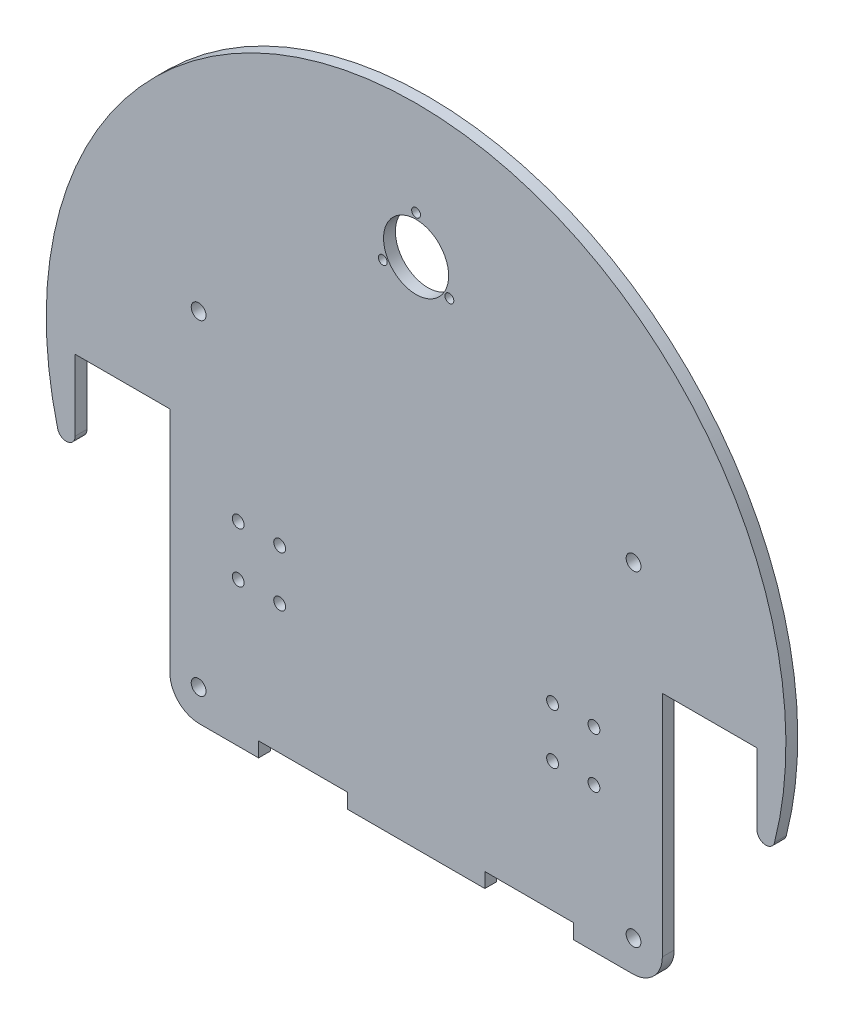
SolidWorks part; units mm, degrees
ref_plane "Front Plane" through (0, 0, 0) normal (0, 0, 1) x (1, 0, 0)
ref_plane "Top Plane" through (0, 0, 0) normal (0, 1, 0) x (1, 0, 0)
ref_plane "Right Plane" through (0, 0, 0) normal (1, 0, 0) x (0, 0, -1)
sketch "Sketch1" plane through (0, 0, 0) normal (0, 0, 1) x (1, 0, 0)
  line L0 (-115.2338, -48.4373) -> (-115.2338, -6.094)
  line L1 (-115.2338, -6.094) -> (-83.2338, -6.094)
  line L2 (-83.2338, -6.094) -> (-83.2338, -93.2584)
  line L3 (0, 125) -> (0, -125) construction
  line L4 (115.2338, -48.4373) -> (115.2338, -6.094)
  line L5 (115.2338, -6.094) -> (83.2338, -6.094)
  line L6 (83.2338, -6.094) -> (83.2338, -93.2584)
  arc A0 (-83.2338, -93.2584) -> (83.2338, -93.2584) centre (0, 0) ccw
  circle A1 centre (0, 80) radius 11
  arc A2 (115.2338, -48.4373) -> (-115.2338, -48.4373) centre (0, 0) ccw
  point P14 (-116.2147, -46.0342)
  point P15 (-81.8301, -6.5797)
  dimension "D1" = 250
  dimension "D2" = 22
  dimension "D3" = 80
  dimension "D4" = 32
extrude "Boss-Extrude1" add sketch "Sketch1" along normal blind 4
sketch "Sketch2" plane through (0, 0, 4) normal (0, 0, 1) x (1, 0, 0)
  circle A0 centre (0, 92.9904) radius 1.5
  circle A1 centre (11.25, 73.5048) radius 1.5
  circle A2 centre (-11.25, 73.5048) radius 1.5
  dimension "D1" = 3
extrude "Cut-Extrude1" cut sketch "Sketch2" against normal blind 10
sketch "Sketch3" plane through (0, 0, 4) normal (0, 0, 1) x (1, 0, 0)
  line L0 (-83.2338, -93.2584) -> (83.2338, -93.2584)
  arc A0 (-83.2338, -93.2584) -> (83.2338, -93.2584) centre (0, 0) ccw construction
  arc A1 (-83.2338, -93.2584) -> (83.2338, -93.2584) centre (0, 0) ccw
extrude "Cut-Extrude2" cut sketch "Sketch3" against normal blind 10
fillet "Fillet1" radius 10 2 edges at (-83.2338, -93.2584, 2) (83.2338, -93.2584, 2)
fillet "Fillet3" radius 3 2 edges at (115.2338, -48.4373, 2) (-115.2338, -48.4373, 2)
sketch "Sketch5" plane through (0, 0, 4) normal (0, 0, 1) x (1, 0, 0)
  line L0 (73.2338, -93.2584) -> (-73.2338, -93.2584) construction
  line L1 (53.2338, -93.2584) -> (23.2338, -93.2584)
  line L2 (53.2338, -93.2584) -> (53.2338, -88.2584)
  line L3 (53.2338, -88.2584) -> (23.2338, -88.2584)
  line L4 (23.2338, -93.2584) -> (23.2338, -88.2584)
  line L5 (83.2338, -83.2584) -> (83.2338, -6.094) construction
  line L6 (0, 0) -> (0, -93.2584) construction
  line L7 (-23.2338, -93.2584) -> (-23.2338, -88.2584)
  line L8 (-53.2338, -88.2584) -> (-23.2338, -88.2584)
  line L9 (-53.2338, -93.2584) -> (-53.2338, -88.2584)
  line L10 (-53.2338, -93.2584) -> (-23.2338, -93.2584)
  dimension "D1" = 30
  dimension "D2" = 5
  dimension "D3" = 30
extrude "Cut-Extrude4" cut sketch "Sketch5" against normal blind 10
sketch "Sketch6" plane through (0, 0, 4) normal (0, 0, 1) x (1, 0, 0)
  circle A0 centre (-73.5, -82.6455) radius 2.5
  circle A1 centre (73.5, -82.6455) radius 2.5
  circle A2 centre (73.5, 27.3545) radius 2.5
  circle A3 centre (-73.5, 27.3545) radius 2.5
  dimension "D1" = 5
extrude "Cut-Extrude5" cut sketch "Sketch6" against normal through all
sketch "Sketch7" plane through (0, 0, 4) normal (0, 0, 1) x (1, 0, 0)
  line L0 (-115.2338, -30.0794) -> (-115.2338, 48.4373)
  arc A0 (121.1412, -30.819) -> (-121.1412, -30.819) centre (0, 0) ccw construction
  arc A1 (-121.1412, -30.819) -> (-115.2338, -30.0794) centre (-118.2338, -30.0794) ccw construction
  arc A2 (-115.2338, 48.4373) -> (-121.1412, -30.819) centre (0, 0) ccw
  arc A3 (-121.1412, -30.819) -> (-115.2338, -30.0794) centre (-118.2338, -30.0794) ccw
extrude "Cut-Extrude6" [suppressed] cut sketch "Sketch7" against normal blind 10
mirror "Mirror1" [suppressed] about plane through (0, 0, 0) normal (1, 0, 0)
sketch "Sketch8" plane through (0, 0, 4) normal (0, 0, 1) x (1, 0, 0)
  circle A0 centre (46.1155, -27.4976) radius 2
  circle A1 centre (46.1155, -44.4976) radius 2
  circle A2 centre (60.1155, -44.4976) radius 2
  circle A3 centre (60.1155, -27.4976) radius 2
  dimension "D1" = 4
extrude "Cut-Extrude7" cut sketch "Sketch8" against normal through all
ref_plane "Plane1" through (0, 0, 0) normal (-1, 0, 0) x (0, 0, 1)
mirror "Mirror2" about plane through (0, 0, 0) normal (-1, 0, 0) of "Cut-Extrude7"
